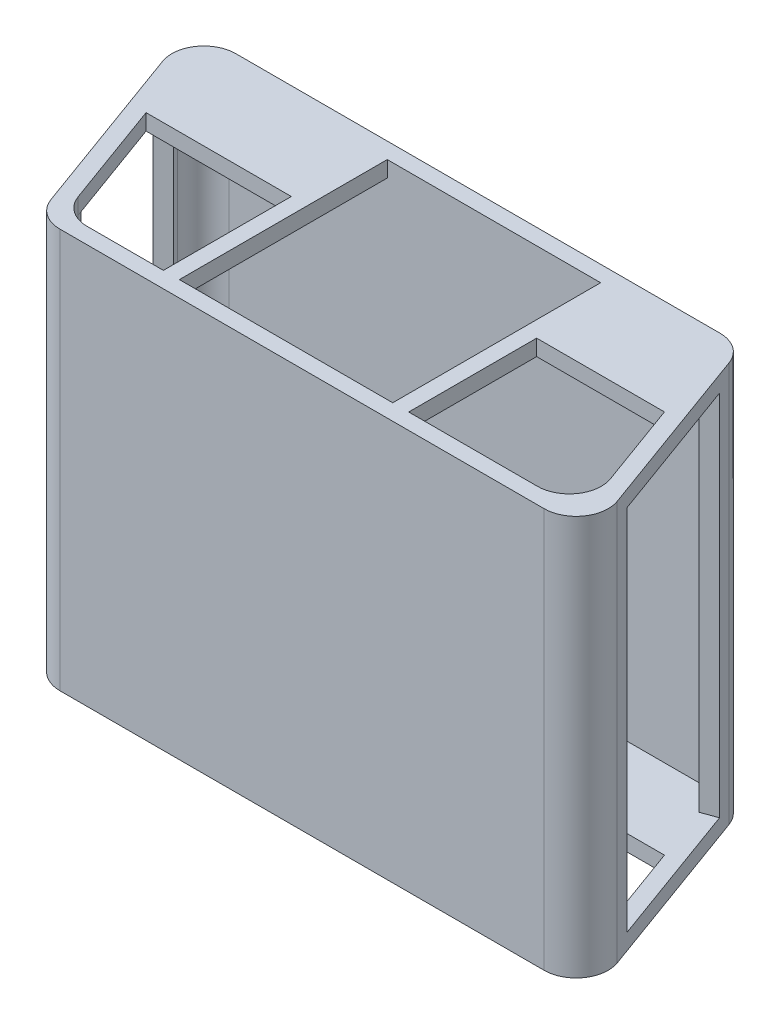
SolidWorks part; units mm, degrees
material "Plain Carbon Steel"
ref_plane "Front Plane" through (0, 0, 0) normal (0, 0, 1) x (1, 0, 0)
ref_plane "Top Plane" through (0, 0, 0) normal (0, 1, 0) x (1, 0, 0)
ref_plane "Right Plane" through (0, 0, 0) normal (1, 0, 0) x (0, 0, -1)
sketch "Sketch1" plane through (0, 0, 0) normal (0, 1, 0) x (1, 0, 0)
  line L0 (0, 0) -> (6056.75, 0)
  line L1 (6432.6252, -263.1926) -> (7233.3436, -2463.1973)
  line L2 (6857.4656, -3000.0027) -> (800.7156, -3000.0027)
  line L3 (424.8404, -2736.8101) -> (-375.878, -536.8054)
  arc A0 (6056.75, 0) -> (6432.6252, -263.1926) centre (6056.75, -399.997) cw
  arc A1 (6857.4656, -3000.0027) -> (7233.3436, -2463.1973) centre (6857.4656, -2600.0027) ccw
  arc A2 (424.8404, -2736.8101) -> (800.7156, -3000.0027) centre (800.7156, -2600.0057) ccw
  arc A3 (-375.878, -536.8054) -> (0, 0) centre (0, -400) cw
  dimension "D1" = 400
  dimension "D2" = 6056.75
  dimension "D3" = 2341.19
  dimension "D4" = 2341.19
  dimension "D5" = 6056.75
  dimension "D6" = 655.32
  dimension "D7" = 458.86
  dimension "D8" = 655.32
  dimension "D9" = 250
extrude "Boss-Extrude1" add sketch "Sketch1" along normal blind 200
sketch "Sketch2" plane through (0, 0, 0) normal (0, -1, 0) x (1, 0, 0)
  line L0 (78.3357, 1200.0027) -> (564.884, 2536.8129)
  line L1 (-375.878, 536.8054) -> (424.8404, 2736.8101) construction
  line L2 (78.3357, 1200.0027) -> (1894.7157, 1200.0027)
  line L3 (1894.7157, 1200.0027) -> (1894.7157, 2800.0027)
  line L4 (1894.7157, 2800.0027) -> (940.7603, 2800.0027)
  line L5 (800.7156, 3000.0027) -> (6857.4656, 3000.0027) construction
  line L7 (2094.7157, 2800.0027) -> (4762.7657, 2800.0027)
  line L8 (2094.7157, 2800.0027) -> (2094.7157, 200.0027)
  line L9 (2094.7157, 200.0027) -> (4762.7657, 200.0027)
  line L10 (4762.7657, 2800.0027) -> (4762.7657, 200.0027)
  line L11 (4962.7657, 2800.0027) -> (4962.7657, 1200.0085)
  line L12 (4962.7657, 1200.0085) -> (6560.7557, 1200.0085)
  line L13 (6560.7557, 1200.0085) -> (6947.7162, 2263.1973)
  line L14 (7233.3436, 2463.1973) -> (6432.6252, 263.1926) construction
  line L15 (4962.7657, 2800.0027) -> (6571.8382, 2800.0027)
  arc A0 (564.884, 2536.8129) -> (940.7603, 2800.0027) centre (940.7603, 2400.0027) cw
  arc A1 (6571.8382, 2800.0027) -> (6947.7162, 2263.1973) centre (6571.8382, 2400.0027) cw
  dimension "D6" = 400
  dimension "D15" = 400
  dimension "D1" = 200
  dimension "D2" = 1422.6
  dimension "D3" = 1816.38
  dimension "D4" = 1600
  dimension "D5" = 200
  dimension "D7" = 2668.05
  dimension "D8" = 2600
  dimension "D9" = 200
  dimension "D10" = 200
  dimension "D11" = 200
  dimension "D12" = 1597.99
  dimension "D13" = 200
  dimension "D14" = 200
extrude "Cut-Extrude1" cut sketch "Sketch2" against normal blind 230
sketch "Sketch3" plane through (0, 200, 0) normal (0, 1, 0) x (1, 0, 0)
  line L0 (0, 0) -> (6056.75, 0)
  line L1 (6432.6252, -263.1926) -> (7233.3436, -2463.1973)
  line L2 (6857.4656, -3000.0027) -> (800.7156, -3000.0027)
  line L3 (424.8404, -2736.8101) -> (-375.878, -536.8054)
  line L4 (564.884, -2536.8129) -> (-147.9844, -578.2576)
  line L5 (116.871, -200.0027) -> (6024.5743, -200.0027)
  line L6 (2094.7157, -200.0027) -> (4762.7657, -200.0027) construction
  line L7 (6255.692, -361.8343) -> (6947.7162, -2263.1973)
  line L8 (6560.7557, -1200.0085) -> (6947.7162, -2263.1973) construction
  line L9 (6571.8382, -2800.0027) -> (940.7603, -2800.0027)
  arc A0 (6056.75, 0) -> (6432.6252, -263.1926) centre (6056.75, -399.997) cw
  arc A1 (7233.3436, -2463.1973) -> (6857.4656, -3000.0027) centre (6857.4656, -2600.0027) cw
  arc A2 (800.7156, -3000.0027) -> (424.8404, -2736.8101) centre (800.7156, -2600.0057) cw
  arc A3 (-375.878, -536.8054) -> (0, 0) centre (0, -400) cw
  arc A4 (-147.9844, -578.2576) -> (116.871, -200.0027) centre (116.871, -481.8564) cw
  arc A5 (6024.5743, -200.0027) -> (6255.692, -361.8343) centre (6024.5743, -445.9524) cw
  arc A6 (6947.7162, -2263.1973) -> (6571.8382, -2800.0027) centre (6571.8382, -2400.0027) cw
  arc A7 (940.7603, -2800.0027) -> (564.884, -2536.8129) centre (940.7603, -2400.0027) cw
extrude "Boss-Extrude2" add sketch "Sketch3" along normal blind 4600
ref_plane "Plane1" through (0, 2500, 0) normal (0, 1, 0) x (1, 0, 0)
mirror "Mirror2" about plane through (0, 2500, 0) normal (0, 1, 0) of "Boss-Extrude1", "Cut-Extrude1"
sketch "Sketch4" plane through (5595.5934, 0, -2036.5843) normal (0.9397, 0, -0.342) x (-0.342, 0, -0.9397)
  line L0 (-4788.5551, 5000) -> (-2447.3651, 5000) construction
  line L1 (-4588.5551, 4800) -> (-2647.3651, 4800)
  line L2 (-4588.5551, 4800) -> (-4588.5551, 200)
  line L3 (-4588.5551, 200) -> (-2647.3651, 200)
  line L4 (-2647.3651, 4800) -> (-2647.3651, 200)
  line L5 (-4788.5551, 5000) -> (-4788.5551, 0) construction
  line L6 (-2447.3651, 5000) -> (-2447.3651, 0) construction
  line L7 (-4788.5551, 0) -> (-2447.3651, 0) construction
  dimension "D1" = 200
  dimension "D2" = 200
  dimension "D3" = 200
  dimension "D4" = 200
extrude "Cut-Extrude2" cut sketch "Sketch4" against normal blind 400
sketch "Sketch5" plane through (-504.4334, 0, 183.5947) normal (-0.9397, 0, 0.342) x (0.342, 0, 0.9397)
  line L0 (375.878, 5000) -> (2717.068, 5000) construction
  line L1 (575.878, 4800) -> (2517.068, 4800)
  line L2 (575.878, 4800) -> (575.878, 200)
  line L3 (575.878, 200) -> (2517.068, 200)
  line L4 (2517.068, 4800) -> (2517.068, 200)
  line L5 (375.878, 5000) -> (375.878, 0) construction
  line L6 (375.878, 0) -> (2717.068, 0) construction
  line L7 (2717.068, 5000) -> (2717.068, 0) construction
  dimension "D1" = 200
  dimension "D2" = 200
  dimension "D3" = 200
  dimension "D4" = 200
extrude "Cut-Extrude3" cut sketch "Sketch5" against normal blind 400
